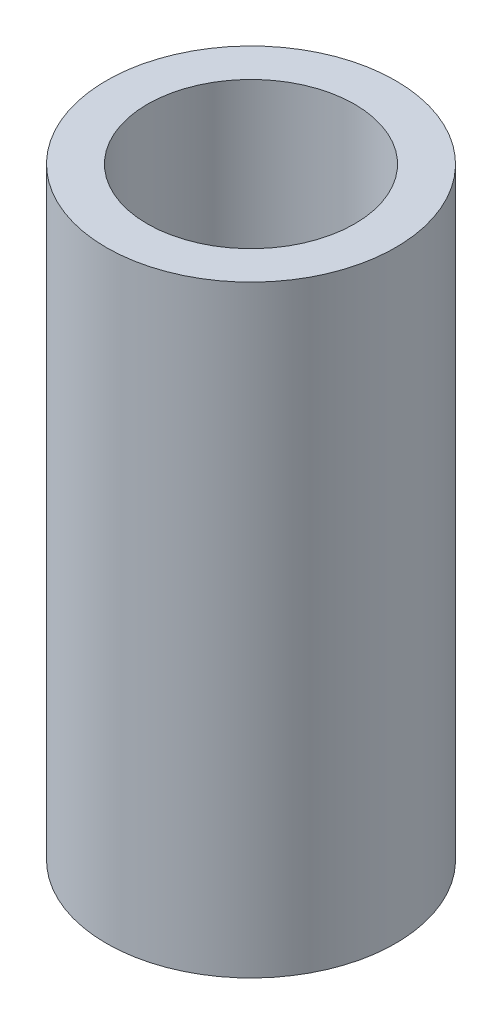
SolidWorks part; units mm, degrees
ref_plane "Alzado" through (0, 0, 0) normal (0, 0, 1) x (1, 0, 0)
ref_plane "Planta" through (0, 0, 0) normal (0, 1, 0) x (1, 0, 0)
ref_plane "Vista lateral" through (0, 0, 0) normal (1, 0, 0) x (0, 0, -1)
sketch "Croquis1" plane through (0, 0, 0) normal (0, 1, 0) x (1, 0, 0)
  circle A0 centre (0, 0) radius 6
  circle A1 centre (0, 0) radius 4.3
extrude "Saliente-Extruir1" add sketch "Croquis1" along normal blind 25
